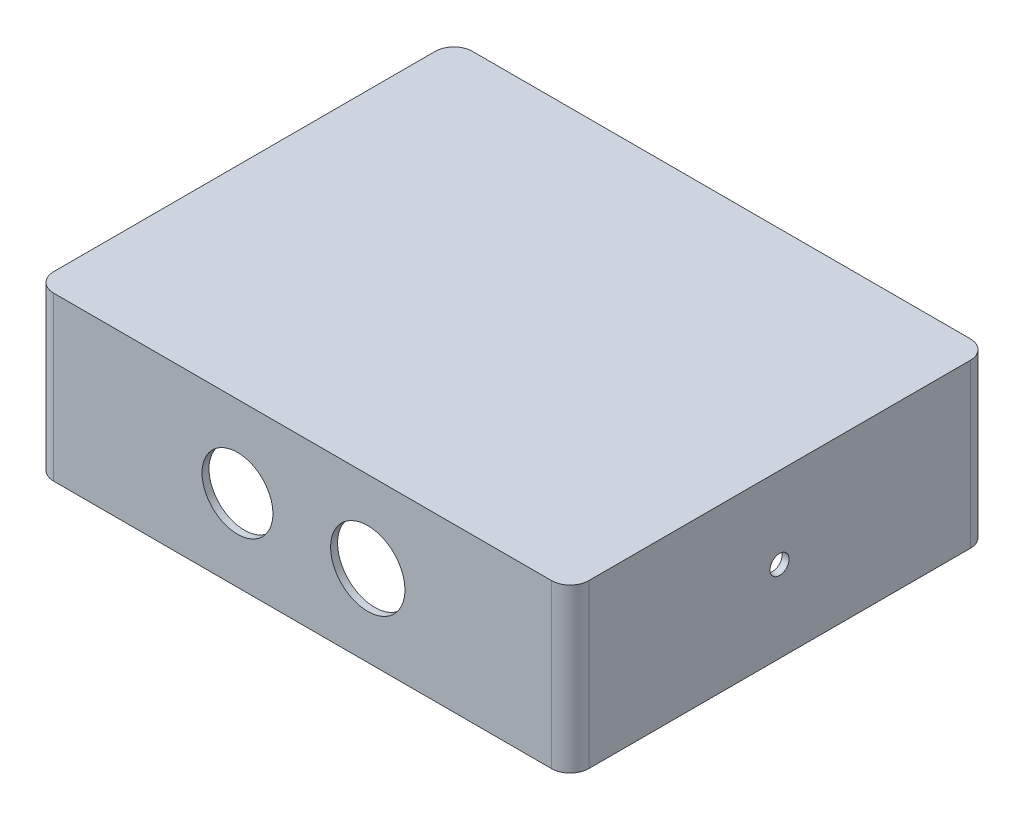
SolidWorks part; units mm, degrees
material "ABS"
ref_plane "Спереди" through (0, 0, 0) normal (0, 0, 1) x (1, 0, 0)
ref_plane "Сверху" through (0, 0, 0) normal (0, 1, 0) x (1, 0, 0)
ref_plane "Справа" through (0, 0, 0) normal (1, 0, 0) x (0, 0, -1)
other "Configuration Table"
sketch "Эскиз1" plane through (0, 0, 0) normal (0, 1, 0) x (1, 0, 0)
  line L0 (-115, 90) -> (0, 0) construction
  line L1 (0, 0) -> (-115, 0)
  line L2 (0, 0) -> (0, 90)
  line L3 (0, 90) -> (-115, 90)
  line L4 (-115, 0) -> (-115, 90)
  line L5 (0, 90) -> (-115, 0) construction
  line L7 (-113.5, 88.5) -> (-1.5, 88.5)
  line L8 (-113.5, 88.5) -> (-113.5, 1.5)
  line L9 (-113.5, 1.5) -> (-1.5, 1.5)
  line L10 (-1.5, 88.5) -> (-1.5, 1.5)
  line L11 (-113.5, 88.5) -> (-1.5, 1.5) construction
  line L12 (-113.5, 1.5) -> (-1.5, 88.5) construction
  point P5 (-57.5, 45)
  dimension "D1" = 90
  dimension "D2" = 115
  dimension "D3" = 87
  dimension "D4" = 112
extrude "Бобышка-Вытянуть1" add sketch "Эскиз1" along normal blind 35
sketch "Эскиз3" plane through (0, 35, 0) normal (0, 1, 0) x (1, 0, 0)
  line L1 (-115, 90) -> (0, 90)
  line L2 (-115, 90) -> (-115, 0)
  line L3 (-115, 0) -> (0, 0)
  line L4 (0, 90) -> (0, 0)
extrude "Бобышка-Вытянуть2" add sketch "Эскиз3" against normal blind 2
sketch "Эскиз4" plane through (0, 33, 0) normal (0, -1, 0) x (1, 0, 0)
  line L2 (-113.5, -1.5) -> (-93.5, -1.5)
  line L3 (-113.5, -1.5) -> (-113.5, -11.5)
  line L4 (-113.5, -11.5) -> (-93.5, -11.5)
  line L5 (-93.5, -1.5) -> (-93.5, -11.5)
  line L6 (-113.5, -88.5) -> (-93.5, -88.5)
  line L7 (-113.5, -88.5) -> (-113.5, -78.5)
  line L8 (-113.5, -78.5) -> (-93.5, -78.5)
  line L9 (-93.5, -88.5) -> (-93.5, -78.5)
  line L10 (-1.5, -88.5) -> (-21.5, -88.5)
  line L11 (-1.5, -88.5) -> (-1.5, -78.5)
  line L12 (-1.5, -78.5) -> (-21.5, -78.5)
  line L13 (-21.5, -88.5) -> (-21.5, -78.5)
  line L14 (-1.5, -1.5) -> (-21.5, -1.5)
  line L15 (-1.5, -1.5) -> (-1.5, -11.5)
  line L16 (-1.5, -11.5) -> (-21.5, -11.5)
  line L17 (-21.5, -1.5) -> (-21.5, -11.5)
  dimension "D1" = 20
  dimension "D2" = 10
  dimension "D3" = 20
  dimension "D4" = 10
  dimension "D5" = 20
  dimension "D6" = 10
  dimension "D7" = 20
  dimension "D8" = 10
extrude "Бобышка-Вытянуть3" add sketch "Эскиз4" along normal blind 33
fillet "Скругление1" radius 4 12 edges at (-21.5, 16.5, -78.5) (-1.5, 16.5, -78.5) (-21.5, 16.5, -88.5) (-93.5, 16.5, -11.5) (-93.5, 16.5, -1.5) (-113.5, 16.5, -11.5) (-21.5, 16.5, -1.5) (-21.5, 16.5, -11.5) (-1.5, 16.5, -11.5) (-93.5, 16.5, -78.5) (-113.5, 16.5, -78.5) (-93.5, 16.5, -88.5)
sketch "Эскиз5" plane through (0, 0, 0) normal (0, -1, 0) x (1, 0, 0)
  line L0 (-115, 0) -> (0, -90) construction
  line L1 (0, -90) -> (0, 0) construction
  line L2 (0, 0) -> (-115, -90) construction
fillet "Скругление2" radius 4 4 edges at (0, 17.5, 0) (0, 17.5, -90) (-115, 17.5, -90) (-115, 17.5, 0)
sketch "Эскиз6" plane through (0, 0, 0) normal (0, -1, 0) x (1, 0, 0)
  line L4 (-115, 0) -> (0, -90) construction
  line L6 (0, 0) -> (-115, -90) construction
  circle A0 centre (-107.9125, -5.5468) radius 2.5
  circle A1 centre (-7.0875, -84.4532) radius 2.5
  circle A2 centre (-107.9125, -84.4532) radius 2.5
  circle A3 centre (-7.0875, -5.5468) radius 2.5
  dimension "D2" = 5
  dimension "D6" = 5
  dimension "D8" = 5
extrude "Вырез-Вытянуть1" cut sketch "Эскиз6" against normal blind 33
sketch "Эскиз7" plane through (-115, 0, 0) normal (-1, 0, 0) x (0, 0, 1)
  line L0 (-86, 35) -> (-4, 0) construction
  line L1 (-4, 0) -> (-4, 35) construction
  line L2 (-4, 35) -> (-86, 0) construction
  circle A0 centre (-45, 17.5) radius 2.05
  dimension "D1" = 4.1
extrude "Вырез-Вытянуть2" cut sketch "Эскиз7" against normal blind 170
sketch "Эскиз8" plane through (0, 0, -90) normal (0, 0, -1) x (-1, 0, 0)
  line L0 (4, 35) -> (51.2174, 19.5551) construction
  line L1 (111, 0) -> (111, 35) construction
  line L2 (111, 35) -> (64.2045, 19.6931) construction
  line L3 (4, 0) -> (57.5, 17.5) construction
  line L5 (4, 35) -> (4, 0) construction
  line L6 (4, 17.5) -> (8.5, 17.5) construction
  line L11 (8.5, 17.5) -> (4, 17.5) construction
  line L14 (57.5, 17.5) -> (111, 0) construction
  line L15 (57.5, 17.5) -> (4, 0) construction
  circle A1 centre (43.5, 17.5) radius 7.9863
  circle A2 centre (71.5, 17.5) radius 7.618
  dimension "D1" = 14
  dimension "D2" = 14
extrude "Вырез-Вытянуть3" cut sketch "Эскиз8" against normal blind 112
